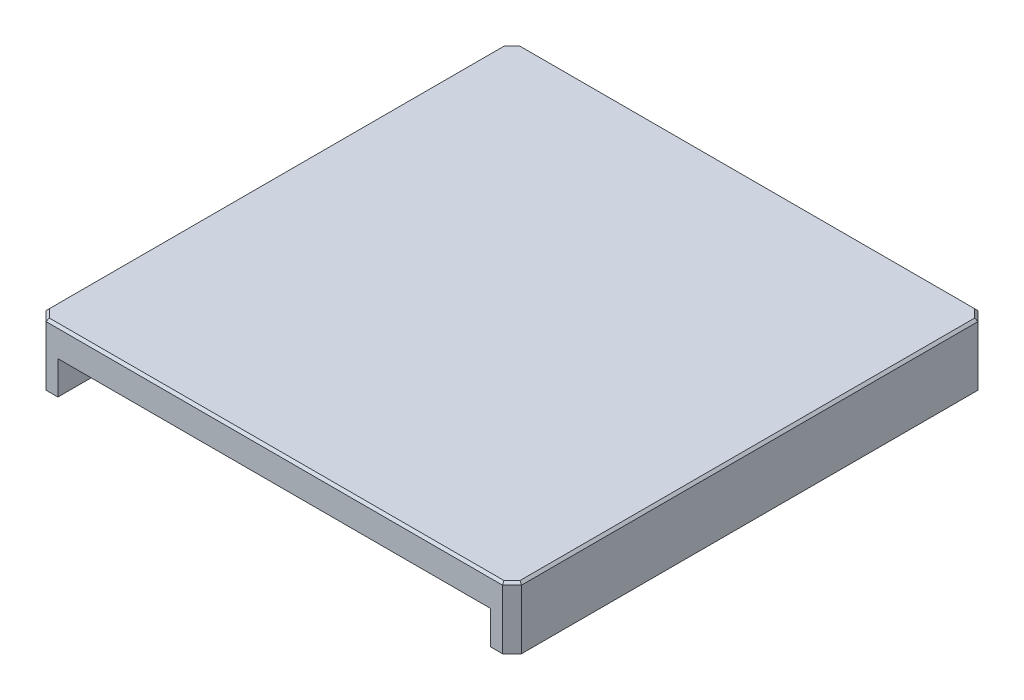
SolidWorks part; units mm, degrees
ref_plane "Front Plane" through (0, 0, 0) normal (0, 0, 1) x (1, 0, 0)
ref_plane "Top Plane" through (0, 0, 0) normal (0, 1, 0) x (1, 0, 0)
ref_plane "Right Plane" through (0, 0, 0) normal (1, 0, 0) x (0, 0, -1)
sketch "Sketch1" plane through (0, 0, 0) normal (0, 0, 1) x (1, 0, 0)
  line L0 (50, 0) -> (50, 13)
  line L1 (0, 0) -> (50, 0) construction
  line L2 (0, 0) -> (0, 13) construction
  line L3 (-50, 13) -> (50, 13) construction
  line L4 (50, 0) -> (50, 13) construction
  line L5 (50, 13) -> (-50, 13)
  line L6 (0, 13) -> (0, 7) construction
  line L7 (-45.5, 7) -> (45.5, 7)
  line L8 (45.5, 7) -> (45.5, 0)
  line L9 (45.5, 0) -> (50, 0)
  line L10 (-50, 0) -> (-50, 13) construction
  line L11 (-45.5, 0) -> (-50, 0)
  line L12 (-45.5, 7) -> (-45.5, 0)
  line L13 (-50, 0) -> (-50, 13)
  dimension "D1" = 50
  dimension "D2" = 13
  dimension "D3" = 4.5
  dimension "D4" = 7
extrude "Boss-Extrude1" add sketch "Sketch1" along normal blind 100
chamfer "Chamfer1" distance 2 angle 45 4 edges at (-50, 6.5, 0) (50, 6.5, 0) (50, 6.5, 100) (-50, 6.5, 100)
chamfer "Chamfer2" distance 0.5 angle 45 8 edges at (49, 13, 1) (50, 13, 50) (49, 13, 99) (0, 13, 100) (-49, 13, 99) (-50, 13, 50) (-49, 13, 1) (0, 13, 0)
